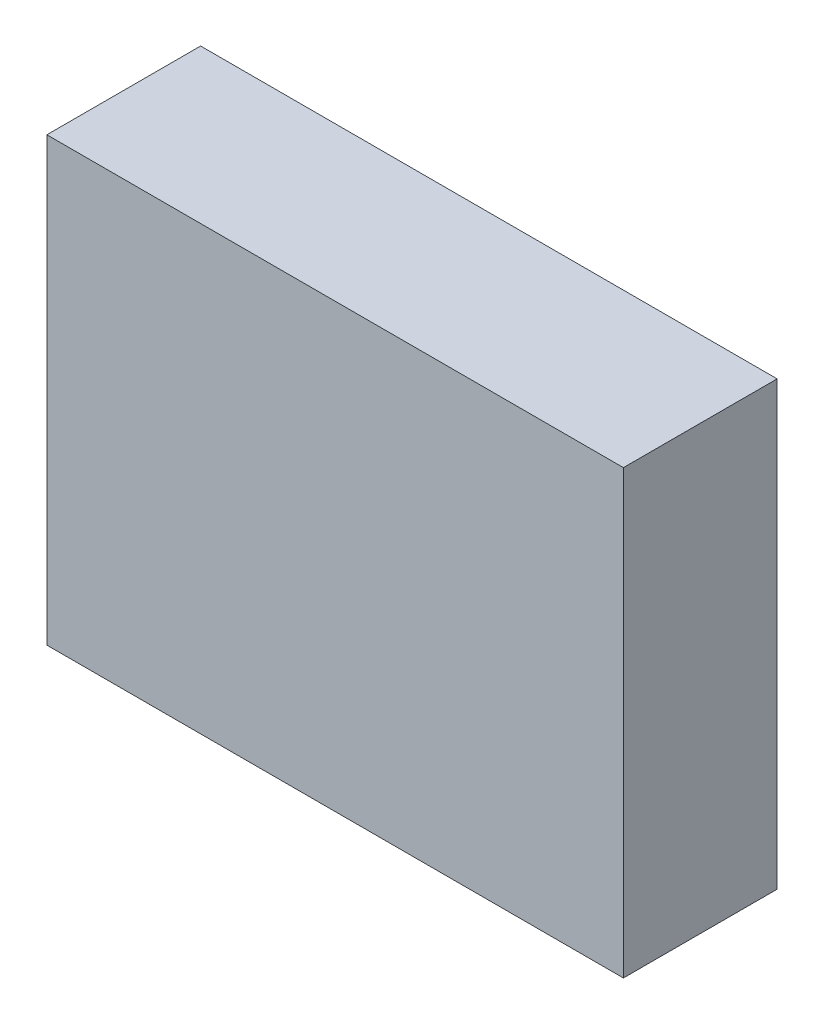
SolidWorks part; units mm, degrees
ref_plane "前视基准面" through (0, 0, 0) normal (0, 0, 1) x (1, 0, 0)
ref_plane "上视基准面" through (0, 0, 0) normal (0, 1, 0) x (1, 0, 0)
ref_plane "右视基准面" through (0, 0, 0) normal (1, 0, 0) x (0, 0, -1)
sketch "草图1" plane through (0, 0, 0) normal (0, 0, 1) x (1, 0, 0)
  line L1 (0, 0) -> (300, 0)
  line L2 (0, 0) -> (0, 230)
  line L3 (0, 230) -> (300, 230)
  line L4 (300, 0) -> (300, 230)
  dimension "D1" = 230
  dimension "D2" = 300
extrude "凸台-拉伸1" add sketch "草图1" along normal blind 80
